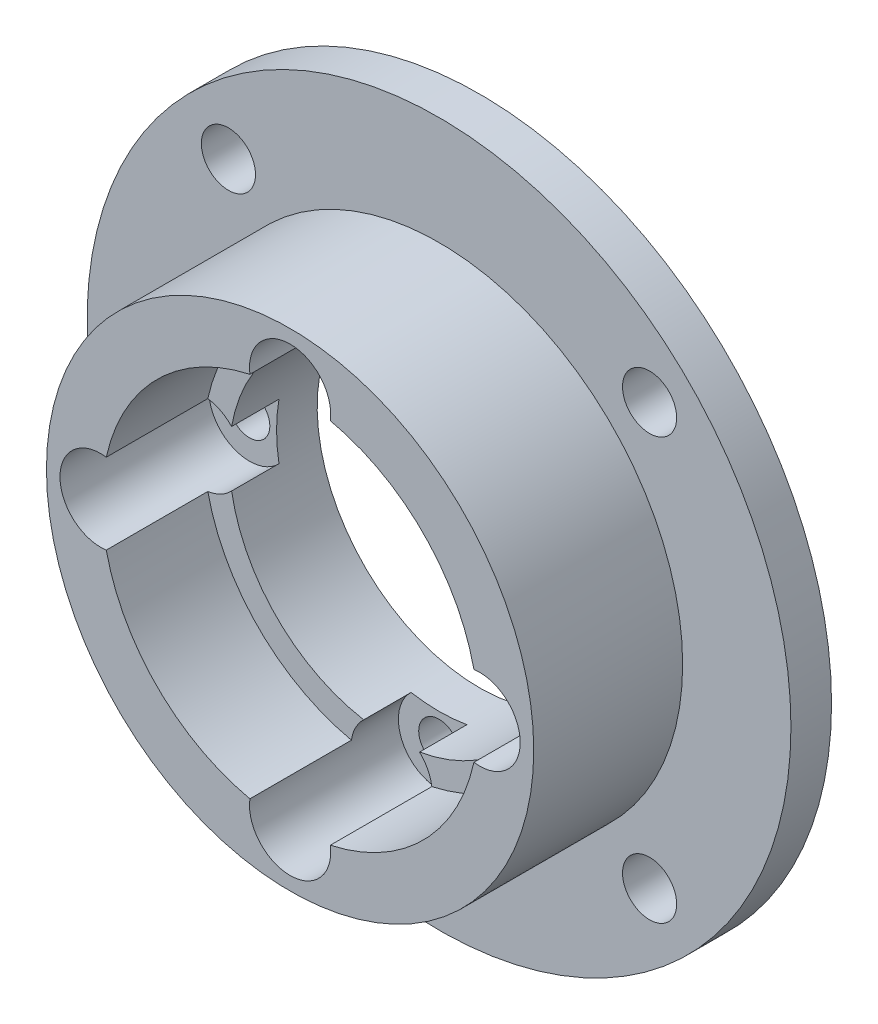
SolidWorks part; units mm, degrees
material "6061 合金"
ref_plane "前视基准面" through (0, 0, 0) normal (0, 0, 1) x (1, 0, 0)
ref_plane "上视基准面" through (0, 0, 0) normal (0, 1, 0) x (1, 0, 0)
ref_plane "右视基准面" through (0, 0, 0) normal (1, 0, 0) x (0, 0, -1)
sketch "草图1" plane through (0, 0, 0) normal (0, 0, 1) x (1, 0, 0)
  line L0 (0, 0) -> (-21.574, 21.574) construction
  circle A0 centre (0, 0) radius 14 construction
  circle A1 centre (0, 0) radius 12
  circle A2 centre (0, 0) radius 26
  circle A3 centre (0, 0) radius 22 construction
  circle A4 centre (-15.5563, 15.5563) radius 2
  circle A5 centre (15.5563, 15.5563) radius 2
  circle A6 centre (15.5563, -15.5563) radius 2
  circle A7 centre (-15.5563, -15.5563) radius 2
  point P18 (0, 0)
  dimension "D1" = 4
extrude "凸台-拉伸1" add sketch "草图1" along normal blind 3
sketch "草图2" plane through (0, 0, 3) normal (0, 0, 1) x (1, 0, 0)
  circle A0 centre (0, 0) radius 13.9
  circle A1 centre (0, 0) radius 18
extrude "凸台-拉伸2" add sketch "草图2" along normal blind 11
sketch "草图3" plane through (0, 0, 0) normal (0, 0, -1) x (-1, 0, 0)
  circle A0 centre (0, 0) radius 14 construction
  circle A1 centre (0, 14) radius 1.5
  circle A2 centre (14, 0) radius 1.5
  circle A3 centre (0, -14) radius 1.5
  circle A4 centre (-14, 0) radius 1.5
  point P14 (0, 0)
  dimension "D1" = 4
extrude "切除-拉伸1" cut sketch "草图3" against normal through all
sketch "草图4" plane through (0, 0, 14) normal (0, 0, 1) x (1, 0, 0)
  circle A0 centre (0, 0) radius 14 construction
  circle A1 centre (0, 14) radius 3
  circle A2 centre (14, 0) radius 3
  circle A3 centre (0, -14) radius 3
  circle A4 centre (-14, 0) radius 3
  point P15 (0, 0)
  dimension "D1" = 4
extrude "切除-拉伸5" cut sketch "草图4" against normal up to surface (11 mm away) up to face at (18, 0, 3)
sketch "草图5" plane through (0, 0, 3) normal (0, 0, 1) x (1, 0, 0)
  arc A0 (-13.5789, -2.9703) -> (-11.8214, -2.0625) centre (-14, 0) ccw
  arc A1 (-2.9703, 13.5789) -> (-2.0625, 11.8214) centre (0, 14) ccw
  arc A2 (13.5789, 2.9703) -> (11.8214, 2.0625) centre (14, 0) ccw
  arc A3 (2.9703, -13.5789) -> (2.0625, -11.8214) centre (0, -14) ccw
  arc A6 (-11.8214, -2.0625) -> (-2.0625, -11.8214) centre (0, 0) ccw
  arc A7 (-11.8214, 2.0625) -> (-13.5789, 2.9703) centre (-14, 0) ccw
  arc A8 (13.5789, -2.9703) -> (13.5789, 2.9703) centre (14, 0) ccw
  arc A9 (13.5789, 2.9703) -> (2.9703, 13.5789) centre (0, 0) ccw
  arc A10 (2.9703, 13.5789) -> (-2.9703, 13.5789) centre (0, 14) ccw
  arc A11 (-2.9703, 13.5789) -> (-13.5789, 2.9703) centre (0, 0) ccw
  arc A12 (-13.5789, 2.9703) -> (-13.5789, -2.9703) centre (-14, 0) ccw
  arc A13 (-13.5789, -2.9703) -> (-2.9703, -13.5789) centre (0, 0) ccw
  arc A14 (-2.9703, -13.5789) -> (2.9703, -13.5789) centre (0, -14) ccw
  arc A15 (2.9703, -13.5789) -> (13.5789, -2.9703) centre (0, 0) ccw
  arc A17 (13.5789, 2.9703) -> (2.9703, 13.5789) centre (0, 0) ccw
  arc A19 (-2.9703, 13.5789) -> (-13.5789, 2.9703) centre (0, 0) ccw
  arc A21 (-13.5789, -2.9703) -> (-2.9703, -13.5789) centre (0, 0) ccw
  arc A23 (2.9703, -13.5789) -> (13.5789, -2.9703) centre (0, 0) ccw
  arc A24 (2.0625, -11.8214) -> (11.8214, -2.0625) centre (0, 0) ccw
  arc A25 (-2.0625, -11.8214) -> (-2.9703, -13.5789) centre (0, -14) ccw
  arc A26 (11.8214, -2.0625) -> (13.5789, -2.9703) centre (14, 0) ccw
  arc A27 (11.8214, 2.0625) -> (2.0625, 11.8214) centre (0, 0) ccw
  arc A28 (-2.0625, 11.8214) -> (-11.8214, 2.0625) centre (0, 0) ccw
  arc A29 (2.0625, 11.8214) -> (2.9703, 13.5789) centre (0, 14) ccw
  dimension "D1" = 0
extrude "凸台-拉伸3" add sketch "草图5" along normal blind 3.5
